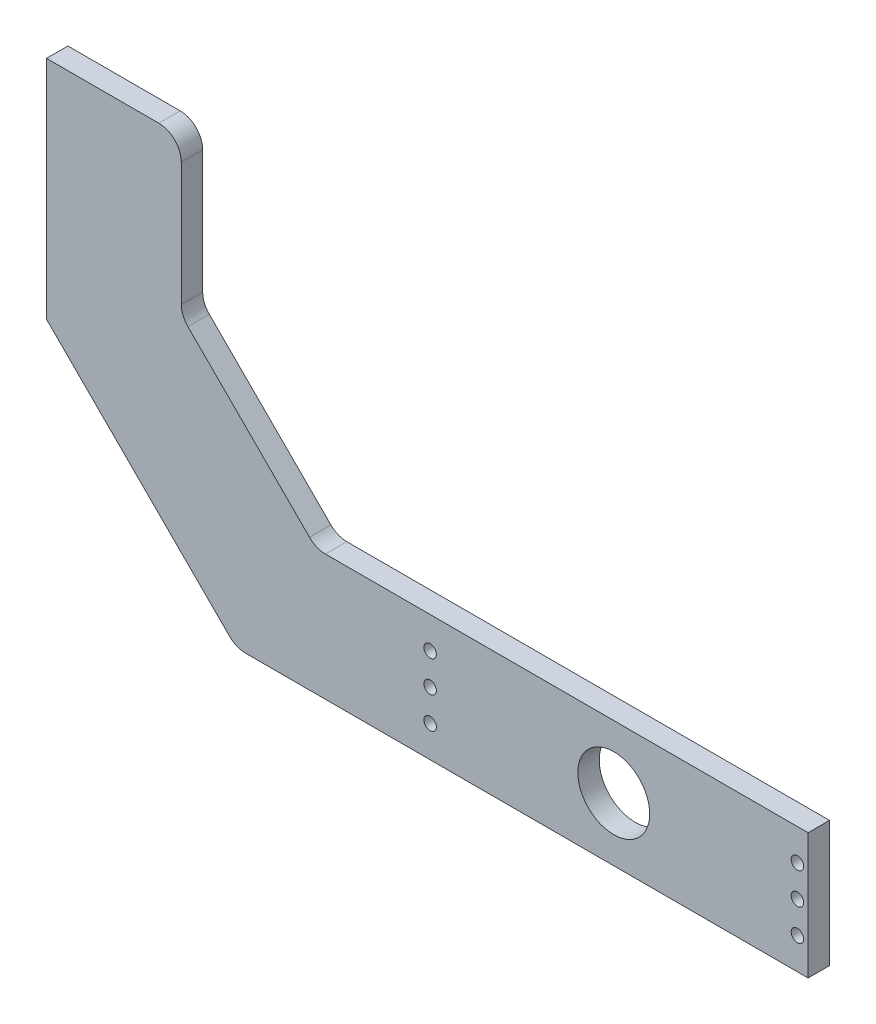
SolidWorks part; units mm, degrees
material "3.0205 (EN AW-1200)"
ref_plane "Plano frontal" through (0, 0, 0) normal (0, 0, 1) x (1, 0, 0)
ref_plane "Plano superior" through (0, 0, 0) normal (0, 1, 0) x (1, 0, 0)
ref_plane "Plano direito" through (0, 0, 0) normal (1, 0, 0) x (0, 0, -1)
sketch "Esboço1" plane through (0, 0, 0) normal (0, 0, 1) x (1, 0, 0)
  line L0 (-114.286, -92.024) -> (224.714, -92.024)
  line L1 (-54.286, 92.976) -> (-114.286, 92.976)
  line L2 (-114.286, 92.976) -> (-114.286, -92.024)
  line L3 (-54.286, 23.976) -> (-54.286, -36.024) construction
  line L4 (-54.286, -36.024) -> (5.714, -36.024) construction
  line L5 (-54.286, 92.976) -> (-54.286, 23.976)
  line L6 (224.714, -92.024) -> (224.714, -36.024)
  line L7 (224.714, -36.024) -> (5.714, -36.024)
  line L8 (5.714, -36.024) -> (-54.286, 23.976)
  dimension "D1" = 219
  dimension "D2" = 56
  dimension "D3" = 339
  dimension "D4" = 185
extrude "Ressalto-extrusão1" add sketch "Esboço1" along normal blind 9.525
sketch "Esboço3" plane through (0, 0, 9.525) normal (0, 0, 1) x (1, 0, 0)
  line L0 (-114.286, -92.024) -> (224.714, -92.024) construction
  circle A1 centre (138.214, -64.024) radius 16
  dimension "D1" = 32
  dimension "D2" = 86.5
  dimension "D3" = 28
extrude "Circulo rolamento" cut sketch "Esboço3" against normal blind 10
sketch "Esboço6" plane through (-114.286, 0, 0) normal (-1, 0, 0) x (0, 0, 1)
  line L0 (4.7625, 92.976) -> (4.7625, -7.024) construction
  line L1 (9.525, 92.976) -> (0, 92.976) construction
  circle A0 centre (4.7625, 67.976) radius 2.5
  circle A1 centre (4.7625, 42.976) radius 2.5
  circle A2 centre (4.7625, 17.976) radius 2.5
  dimension "D1" = 5
  dimension "D2" = 5
  dimension "D3" = 5
  dimension "D4" = 25
  dimension "D5" = 25
extrude "Corte-extrusão4" cut sketch "Esboço6" against normal blind 30
sketch "Esboço9" plane through (0, 0, 9.525) normal (0, 0, 1) x (1, 0, 0)
  line L0 (-29.8419, -92.024) -> (-114.286, -7.5799)
  line L1 (-114.286, -92.024) -> (224.714, -92.024) construction
  line L2 (-114.286, 92.976) -> (-114.286, -92.024) construction
  line L3 (-114.286, -7.5799) -> (-114.286, -92.024)
  line L4 (-114.286, -92.024) -> (-29.8419, -92.024)
  dimension "D1" = 45
extrude "Corte-extrusão6" cut sketch "Esboço9" against normal blind 10
sketch "Esboço10" plane through (0, 0, 9.525) normal (0, 0, 1) x (1, 0, 0)
  line L2 (56.474, -50.024) -> (56.474, -78.024) construction
  line L3 (224.714, -92.024) -> (224.714, -36.024) construction
  line L4 (224.714, -36.024) -> (5.714, -36.024) construction
  circle A0 centre (56.474, -50.024) radius 2.78
  circle A1 centre (56.474, -64.024) radius 2.78
  circle A2 centre (56.474, -78.024) radius 2.78
  dimension "D1" = 5.56
  dimension "D2" = 5.56
  dimension "D3" = 5.56
  dimension "D4" = 14
  dimension "D6" = 168.24
  dimension "D7" = 14
extrude "Corte-extrusão7" cut sketch "Esboço10" against normal blind 10
fillet "Filete1" radius 10 4 edges at (-54.286, 23.976, 4.7625) (5.714, -36.024, 4.7625) (-29.8419, -92.024, 4.7625) (-54.286, 92.976, 4.7625)
sketch "Esboço12" plane through (0, 0, 9.525) normal (0, 0, 1) x (1, 0, 0)
  line L0 (219.954, -50.024) -> (219.954, -78.024) construction
  line L1 (224.714, -36.024) -> (9.8562, -36.024) construction
  line L3 (224.714, -92.024) -> (224.714, -36.024) construction
  line L4 (-25.6997, -92.024) -> (224.714, -92.024) construction
  circle A0 centre (219.954, -78.024) radius 2.78
  circle A1 centre (219.954, -64.024) radius 2.78
  circle A2 centre (219.954, -50.024) radius 2.78
  dimension "D1" = 5.56
  dimension "D2" = 5.56
  dimension "D3" = 5.56
  dimension "D4" = 4.76
  dimension "D5" = 14
  dimension "D7" = 14
extrude "Corte-extrusão8" cut sketch "Esboço12" against normal blind 10
